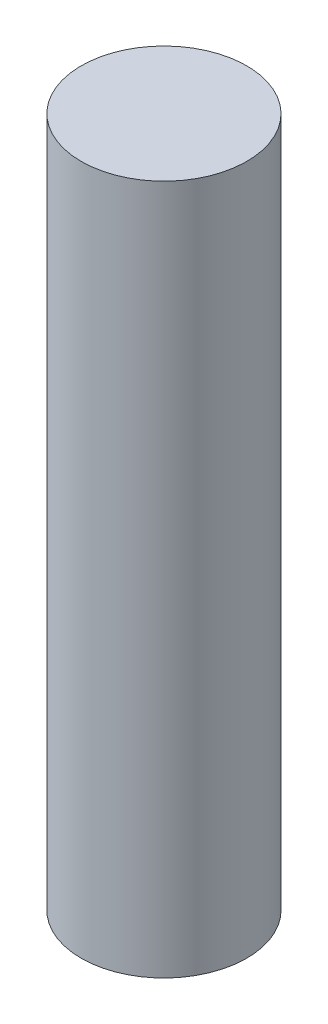
SolidWorks part; units mm, degrees
ref_plane "Front Plane" through (0, 0, 0) normal (0, 0, 1) x (1, 0, 0)
ref_plane "Top Plane" through (0, 0, 0) normal (0, 1, 0) x (1, 0, 0)
ref_plane "Right Plane" through (0, 0, 0) normal (1, 0, 0) x (0, 0, -1)
sketch "Sketch1" plane through (0, 0, 0) normal (0, 1, 0) x (1, 0, 0)
  circle A0 centre (0, 0) radius 2.4
  dimension "D1" = 4.8
extrude "Boss-Extrude1" add sketch "Sketch1" along normal blind 20
